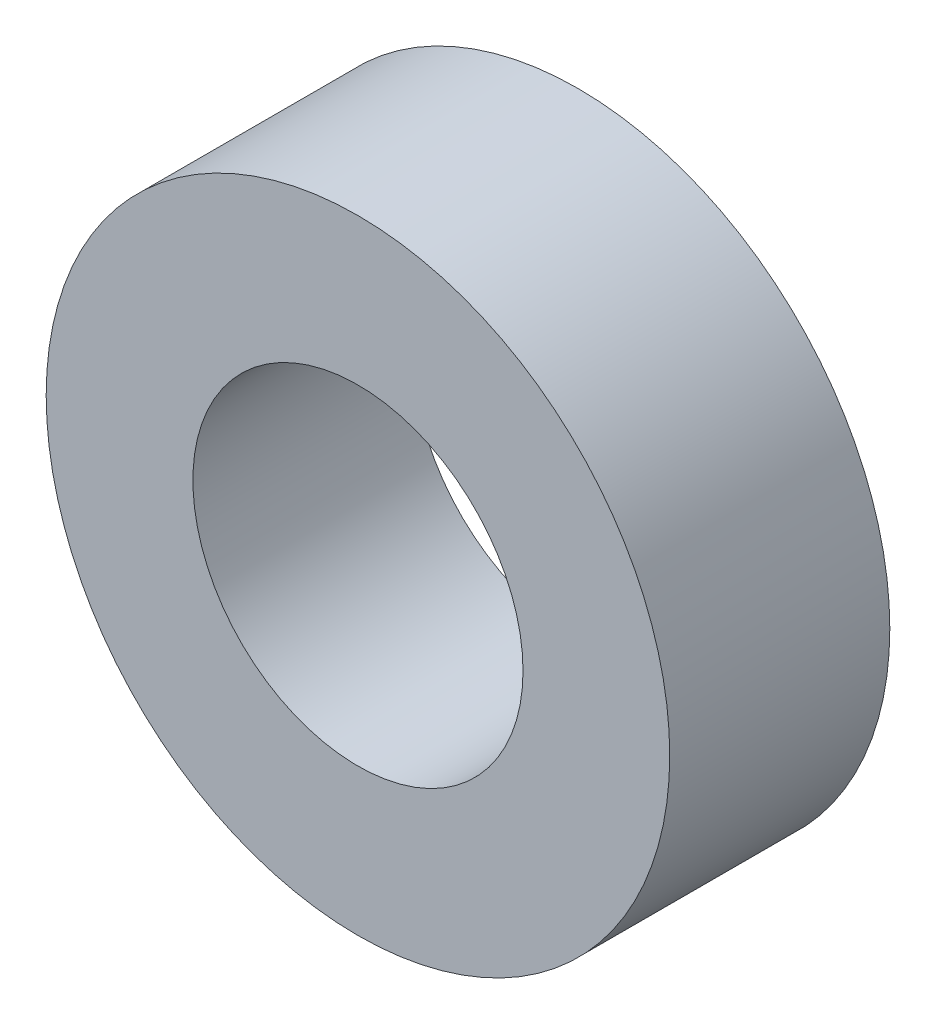
SolidWorks part; units mm, degrees
ref_plane "Plan de face" through (0, 0, 0) normal (0, 0, 1) x (1, 0, 0)
ref_plane "Plan de dessus" through (0, 0, 0) normal (0, 1, 0) x (1, 0, 0)
ref_plane "Plan de droite" through (0, 0, 0) normal (1, 0, 0) x (0, 0, -1)
sketch "Esquisse1" plane through (0, 0, 0) normal (0, 0, 1) x (1, 0, 0)
  circle A0 centre (0, 0) radius 4.5
  circle A1 centre (0, 0) radius 8.5
  dimension "D1" = 9
  dimension "D2" = 4
extrude "Boss.-Extru.1" add sketch "Esquisse1" along normal blind 6
